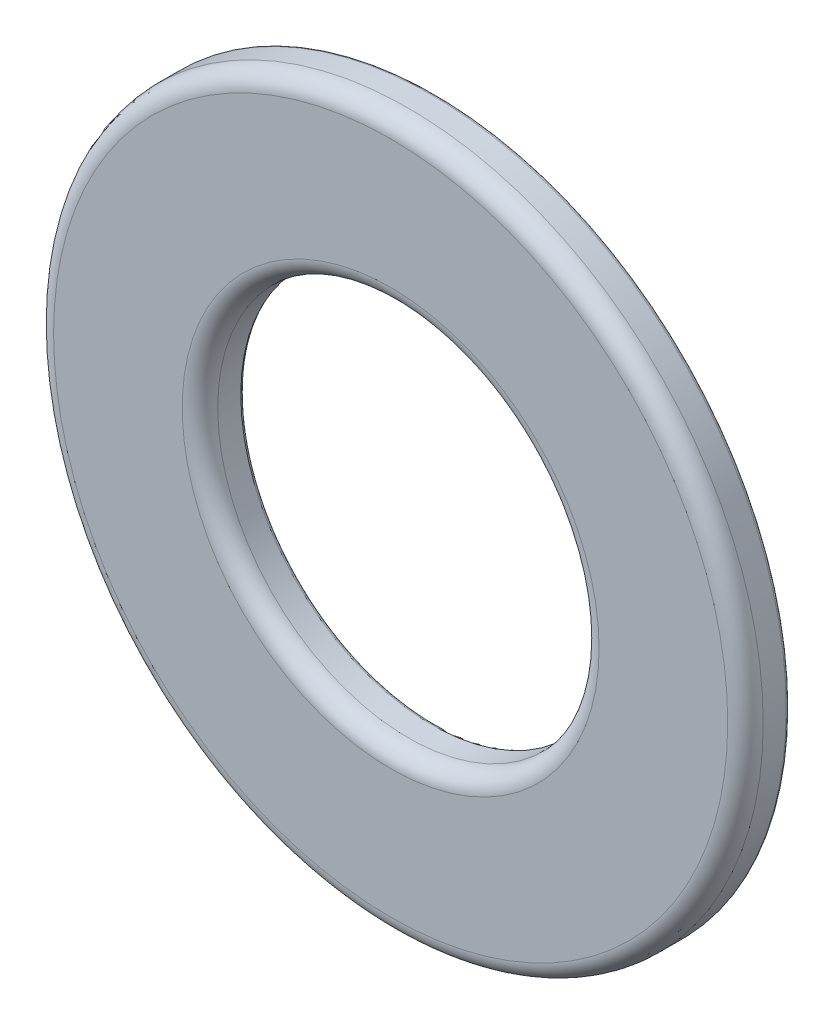
SolidWorks part; units mm, degrees
material "AISI 316 Stainless Steel Sheet (SS)"
ref_plane "Front Plane" through (0, 0, 0) normal (0, 0, 1) x (1, 0, 0)
ref_plane "Top Plane" through (0, 0, 0) normal (0, 1, 0) x (1, 0, 0)
ref_plane "Right Plane" through (0, 0, 0) normal (1, 0, 0) x (0, 0, -1)
sketch "Sketch1" plane through (0, 0, 0) normal (0, 0, 1) x (1, 0, 0)
  circle A0 centre (0, 0) radius 4 construction
  circle A1 centre (0, 0) radius 2.15 construction
  point P6 (0, 4)
  dimension "OD" = 8
  dimension "ID" = 4.3
sketch "Sketch2" plane through (0, 0, 0) normal (1, 0, 0) x (0, 0, -1)
  line L1 (-0.25, 4) -> (0.25, 4) construction
  point P0 (-0.25, 4)
  point P3 (0.25, 4)
  point P11 (-0.25, 4)
  point P13 (0.25, 4)
  dimension "Thickness" = 0.5
sketch "Sketch3" plane through (0, 0, 0) normal (0, 0, 1) x (1, 0, 0)
  circle A0 centre (0, 0) radius 2.15 construction
  circle A1 centre (0, 0) radius 4 construction
  circle A2 centre (0, 0) radius 2.15
  circle A3 centre (0, 0) radius 4
extrude "Boss-Extrude1" add sketch "Sketch3" against normal up to vertex (0.25 mm away) and the other way up to vertex (0.25 mm away) up to point (0, 4, -0.25) other way up to point (0, 4, 0.25)
fillet "Fillet1" radius 0.2 2 edges at (2.15, 0, 0.25) (4, 0, 0.25)
fillet "Fillet3" radius 0.04 2 edges at (4, 0, -0.25) (2.15, 0, -0.25)
equation "\"D1@Fillet1\"=\"OD@Sketch1\"*.025"
equation "\"D1@Fillet2\"=\"OD@Sketch1\"*.02"
equation "\"D1@Fillet3\"=\"OD@Sketch1\"*.005"
